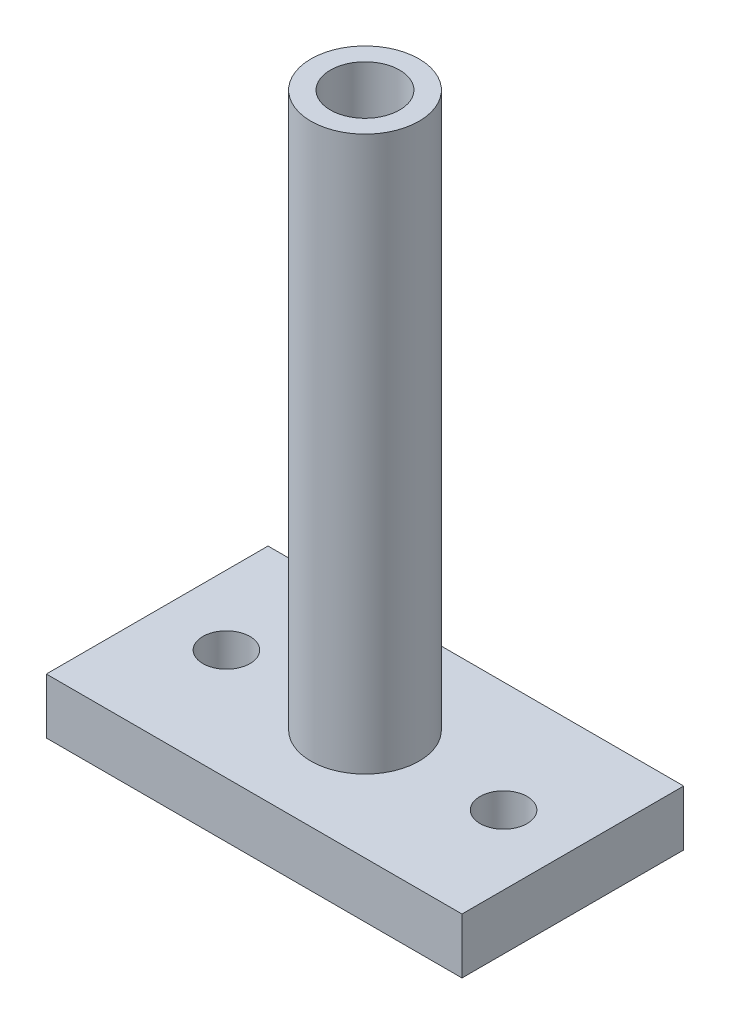
SolidWorks part; units mm, degrees
ref_plane "前视基准面" through (0, 0, 0) normal (0, 0, 1) x (1, 0, 0)
ref_plane "上视基准面" through (0, 0, 0) normal (0, 1, 0) x (1, 0, 0)
ref_plane "右视基准面" through (0, 0, 0) normal (1, 0, 0) x (0, 0, -1)
other "Configuration Table"
sketch "草图1" plane through (0, 0, 0) normal (0, 1, 0) x (1, 0, 0)
  line L0 (7.5, 0) -> (7.5, 8) construction
  line L1 (0, 0) -> (15, 0)
  line L2 (0, 0) -> (0, 8)
  line L3 (0, 8) -> (15, 8)
  line L4 (15, 0) -> (15, 8)
  line L5 (0, 4) -> (15, 4) construction
  circle A0 centre (2.5, 4) radius 0.85
  circle A1 centre (12.5, 4) radius 0.85
  dimension "D3" = 1.7
  dimension "D1" = 15
  dimension "D2" = 8
  dimension "D4" = 5
extrude "凸台-拉伸1" add sketch "草图1" along normal blind 2
sketch "草图2" plane through (0, 2, 0) normal (0, 1, 0) x (1, 0, 0)
  line L0 (7.5, 0) -> (7.5, 8) construction
  line L1 (0, 0) -> (15, 0) construction
  line L2 (15, 8) -> (0, 8) construction
  circle A0 centre (7.5, 4) radius 1.95
  dimension "D1" = 3.9
extrude "凸台-拉伸2" add sketch "草图2" along normal blind 20
sketch "草图3" plane through (0, 22, 0) normal (0, 1, 0) x (1, 0, 0)
  circle A0 centre (7.5, 4) radius 1.25
  dimension "D1" = 2.5
extrude "切除-拉伸1" cut sketch "草图3" against normal blind 5
